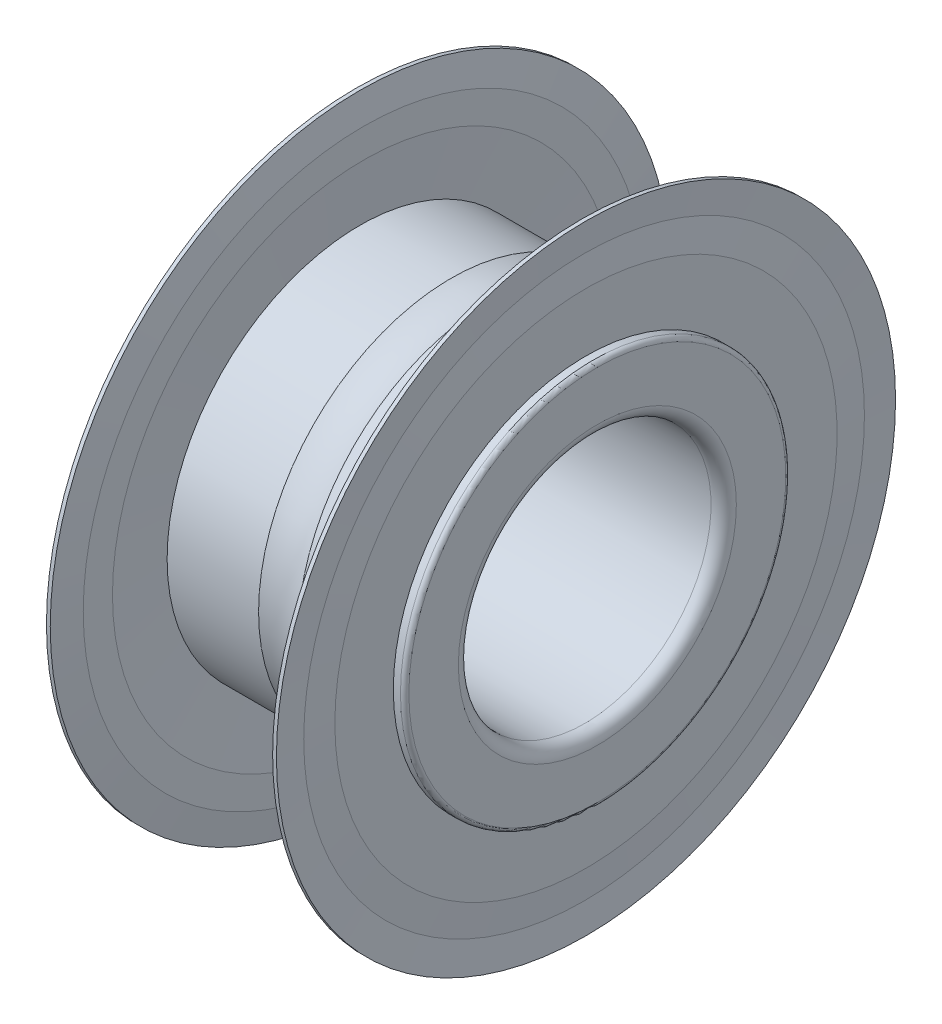
SolidWorks part; units mm, degrees
ref_plane "Ebene vorne" through (0, 0, 0) normal (0, 0, 1) x (1, 0, 0)
ref_plane "Ebene oben" through (0, 0, 0) normal (0, 1, 0) x (1, 0, 0)
ref_plane "Ebene rechts" through (0, 0, 0) normal (1, 0, 0) x (0, 0, -1)
ref_plane "Plane1" through (0, 0, 0) normal (0, 0, 1) x (1, 0, 0)
sketch "Sketch1" plane through (0, 0, 0) normal (0, 0, 1) x (1, 0, 0)
  line L0 (0, 2.9833) -> (0, 2.2)
  line L1 (0.2, 2) -> (3.8, 2)
  line L2 (4, 2.2) -> (4, 2.9833)
  line L3 (3.9333, 3.05) -> (2.3122, 3.05)
  line L4 (1.6878, 3.05) -> (0.0667, 3.05)
  line L5 (50, 0) -> (-50, 0) construction
  arc A0 (0, 2.2) -> (0.2, 2) centre (0.2, 2.2) ccw
  arc A1 (3.8, 2) -> (4, 2.2) centre (3.8, 2.2) ccw
  arc A2 (4, 2.9833) -> (3.9333, 3.05) centre (3.9333, 2.9833) ccw
  arc A3 (2.3122, 3.05) -> (1.6878, 3.05) centre (2, 4) cw
  arc A4 (0.0667, 3.05) -> (0, 2.9833) centre (0.0667, 2.9833) ccw
revolve "Revolve1" add sketch "Sketch1" angle 360 about L5
ref_plane "Plane2" through (0, 0, 0) normal (0, 0, 1) x (1, 0, 0)
sketch "Sketch2" plane through (0, 0, 0) normal (0, 0, 1) x (1, 0, 0)
  line L0 (0.18, 4.9) -> (0.21, 4.4375)
  line L1 (0.21, 4.4375) -> (0.18, 3.975)
  line L2 (0.18, 3.975) -> (0.18, 3.05)
  line L3 (0.18, 3.05) -> (0.24, 3.05)
  line L4 (0.24, 3.05) -> (0.3, 3.975)
  line L5 (0.3, 3.975) -> (0.3, 4.4375)
  line L6 (0.3, 4.4375) -> (0.24, 4.9)
  line L7 (0.24, 4.9) -> (0.18, 4.9)
  line L8 (50, 0) -> (-50, 0) construction
revolve "Revolve2" add sketch "Sketch2" angle 360 about L8
ref_plane "Plane3" through (0, 0, 0) normal (0, 0, 1) x (1, 0, 0)
sketch "Sketch3" plane through (0, 0, 0) normal (0, 0, 1) x (1, 0, 0)
  line L0 (3.7, 4.4375) -> (3.7, 3.975)
  line L1 (3.7, 3.975) -> (3.76, 3.05)
  line L2 (3.76, 3.05) -> (3.82, 3.05)
  line L3 (3.82, 3.05) -> (3.82, 3.975)
  line L4 (3.82, 3.975) -> (3.79, 4.4375)
  line L5 (3.79, 4.4375) -> (3.82, 4.9)
  line L6 (3.82, 4.9) -> (3.76, 4.9)
  line L7 (3.76, 4.9) -> (3.7, 4.4375)
  line L8 (50, 0) -> (-50, 0) construction
revolve "Revolve3" add sketch "Sketch3" angle 360 about L8
